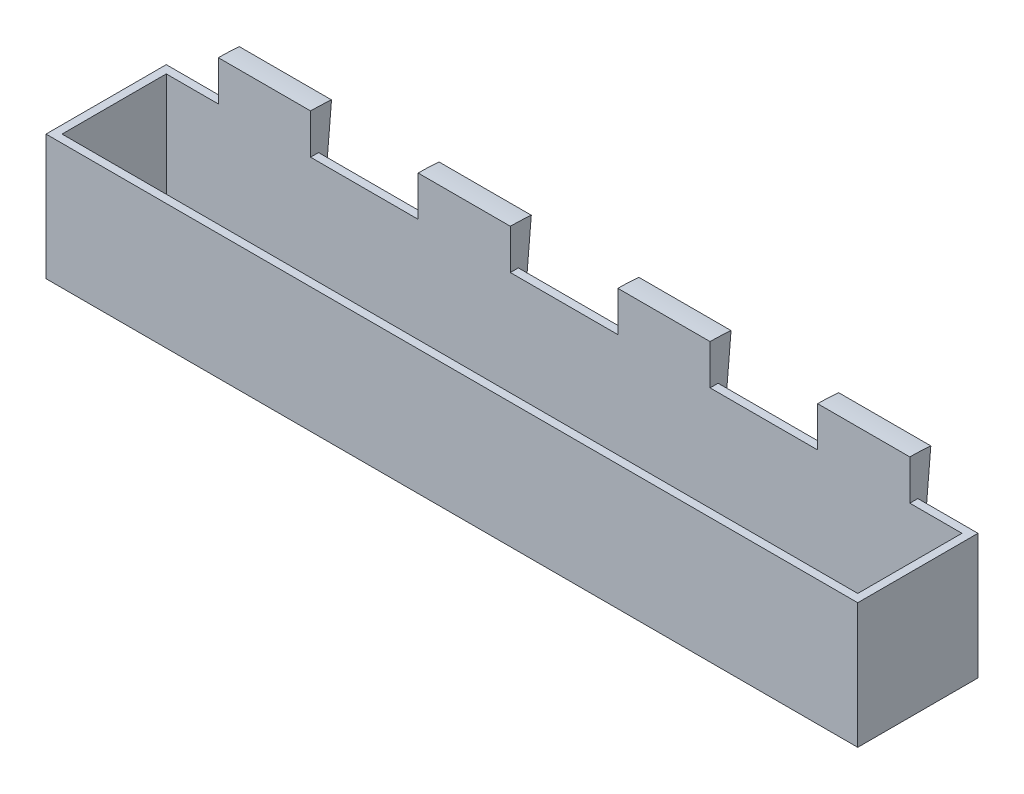
SolidWorks part; units mm, degrees
ref_plane "Front Plane" through (0, 0, 0) normal (0, 0, 1) x (1, 0, 0)
ref_plane "Top Plane" through (0, 0, 0) normal (0, 1, 0) x (1, 0, 0)
ref_plane "Right Plane" through (0, 0, 0) normal (1, 0, 0) x (0, 0, -1)
sketch "Sketch1" plane through (0, 0, 0) normal (0, 1, 0) x (1, 0, 0)
  line L0 (-252.095, 33.02) -> (-252.095, -33.02)
  line L1 (-257.175, 38.1) -> (257.175, 38.1)
  line L2 (-257.175, 38.1) -> (-257.175, -38.1)
  line L3 (-257.175, -38.1) -> (257.175, -38.1)
  line L4 (257.175, 38.1) -> (257.175, -38.1)
  line L5 (-257.175, 38.1) -> (257.175, -38.1) construction
  line L6 (-257.175, -38.1) -> (257.175, 38.1) construction
  line L7 (-252.095, -33.02) -> (252.095, -33.02)
  line L8 (252.095, 33.02) -> (252.095, -33.02)
  line L9 (-252.095, 33.02) -> (252.095, 33.02)
  point P1 (0, 0)
  dimension "D1" = 514.35
  dimension "D2" = 76.2
  dimension "D3" = 5.08
extrude "Boss-Extrude1" add sketch "Sketch1" along normal blind 76.2
sketch "Sketch2" plane through (0, 0, -33.02) normal (0, 0, -1) x (-1, 0, 0)
  line L0 (-219.075, 12.7) -> (-219.075, 101.6)
  line L1 (-219.075, 101.6) -> (-160.655, 101.6)
  line L2 (-160.655, 101.6) -> (-160.655, 12.7)
  line L3 (-160.655, 12.7) -> (-170.815, 12.7)
  line L4 (-170.815, 12.7) -> (-170.815, 91.44)
  line L5 (-170.815, 91.44) -> (-208.915, 91.44)
  line L6 (-208.915, 91.44) -> (-208.915, 12.7)
  line L7 (-208.915, 12.7) -> (-219.075, 12.7)
  line L8 (-257.175, 76.2) -> (257.175, 76.2) construction
  line L9 (-257.175, 76.2) -> (-257.175, 0) construction
  line L10 (-82.3383, 12.7) -> (-92.4983, 12.7)
  line L11 (-92.4983, 12.7) -> (-92.4983, 101.6)
  line L12 (-92.4983, 101.6) -> (-34.0783, 101.6)
  line L13 (-34.0783, 101.6) -> (-34.0783, 12.7)
  line L14 (-34.0783, 12.7) -> (-44.2383, 12.7)
  line L15 (-44.2383, 12.7) -> (-44.2383, 91.44)
  line L16 (-44.2383, 91.44) -> (-82.3383, 91.44)
  line L17 (-82.3383, 91.44) -> (-82.3383, 12.7)
  line L18 (44.2383, 12.7) -> (34.0783, 12.7)
  line L19 (34.0783, 12.7) -> (34.0783, 101.6)
  line L20 (34.0783, 101.6) -> (92.4983, 101.6)
  line L21 (92.4983, 101.6) -> (92.4983, 12.7)
  line L22 (92.4983, 12.7) -> (82.3383, 12.7)
  line L23 (82.3383, 12.7) -> (82.3383, 91.44)
  line L24 (82.3383, 91.44) -> (44.2383, 91.44)
  line L25 (44.2383, 91.44) -> (44.2383, 12.7)
  line L26 (170.815, 12.7) -> (160.655, 12.7)
  line L27 (160.655, 12.7) -> (160.655, 101.6)
  line L28 (160.655, 101.6) -> (219.075, 101.6)
  line L29 (219.075, 101.6) -> (219.075, 12.7)
  line L30 (219.075, 12.7) -> (208.915, 12.7)
  line L31 (208.915, 12.7) -> (208.915, 91.44)
  line L32 (208.915, 91.44) -> (170.815, 91.44)
  line L33 (170.815, 91.44) -> (170.815, 12.7)
  line L34 (257.175, 76.2) -> (257.175, 0) construction
  line L35 (-275.9721, -50.8) -> (113.9284, -50.8) construction
  line L36 (-257.175, 0) -> (257.175, 0) construction
  dimension "D1" = 63.5
  dimension "D2" = 38.1
  dimension "D3" = 88.9
  dimension "D4" = 10.16
  dimension "D5" = 10.16
  dimension "D6" = 38.1
  dimension "D8" = 38.1
  dimension "D9" = 50.8
  dimension "D7" = 4
revolve "Revolve1" add sketch "Sketch2" angle 5 about L35
sketch "Sketch3" plane through (0, 0, -33.02) normal (0, 0, 1) x (1, 0, 0)
  line L1 (-208.915, 91.44) -> (-170.815, 91.44)
  line L2 (-208.915, 91.44) -> (-208.915, 76.2)
  line L3 (-208.915, 76.2) -> (-170.815, 76.2)
  line L4 (-170.815, 91.44) -> (-170.815, 76.2)
  line L5 (-82.3383, 76.2) -> (-44.2383, 76.2)
  line L6 (-82.3383, 76.2) -> (-82.3383, 91.44)
  line L7 (-82.3383, 91.44) -> (-44.2383, 91.44)
  line L8 (-44.2383, 76.2) -> (-44.2383, 91.44)
  line L9 (44.2383, 91.44) -> (82.3383, 91.44)
  line L10 (44.2383, 91.44) -> (44.2383, 76.2)
  line L11 (44.2383, 76.2) -> (82.3383, 76.2)
  line L12 (82.3383, 91.44) -> (82.3383, 76.2)
  line L13 (170.815, 76.2) -> (208.915, 76.2)
  line L14 (170.815, 76.2) -> (170.815, 91.44)
  line L15 (170.815, 91.44) -> (208.915, 91.44)
  line L16 (208.915, 76.2) -> (208.915, 91.44)
extrude "Boss-Extrude2" add sketch "Sketch3" against normal up to surface (5.08 mm away) up to face at (0, 43.654, -38.1)
sketch "Sketch4" plane through (0, 0, 0) normal (0, -1, 0) x (1, 0, 0)
  line L1 (-257.175, 38.1) -> (257.175, 38.1)
  line L2 (-257.175, 38.1) -> (-257.175, -38.1)
  line L3 (-257.175, -38.1) -> (257.175, -38.1)
  line L4 (257.175, 38.1) -> (257.175, -38.1)
extrude "Boss-Extrude3" add sketch "Sketch4" along normal blind 3.175
